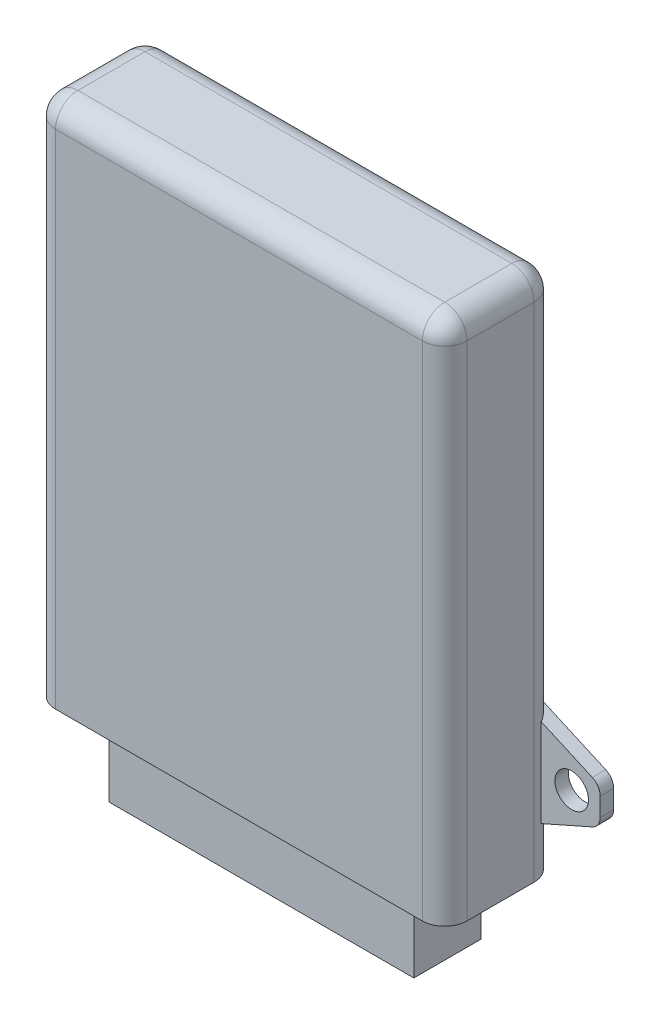
SolidWorks part; units mm, degrees
ref_plane "前视基准面" through (0, 0, 0) normal (0, 0, 1) x (1, 0, 0)
ref_plane "上视基准面" through (0, 0, 0) normal (0, 1, 0) x (1, 0, 0)
ref_plane "右视基准面" through (0, 0, 0) normal (1, 0, 0) x (0, 0, -1)
sketch "草图1" plane through (0, 0, 0) normal (0, 0, 1) x (1, 0, 0)
  line L1 (-37.9333, 65.9947) -> (44.0667, 65.9947)
  line L2 (-42.9333, 60.9947) -> (-42.9333, -51.3053)
  line L3 (-42.9333, -51.3053) -> (49.0667, -51.3053)
  line L4 (49.0667, 60.9947) -> (49.0667, -51.3053)
  arc A0 (49.0667, 60.9947) -> (44.0667, 65.9947) centre (44.0667, 60.9947) ccw
  arc A1 (-42.9333, 60.9947) -> (-37.9333, 65.9947) centre (-37.9333, 60.9947) cw
  point P6 (49.0667, 65.9947)
  point P9 (-42.9333, 65.9947)
  dimension "D3" = 5
  dimension "D1" = 92
  dimension "D2" = 117.3
extrude "凸台-拉伸1" add sketch "草图1" along normal blind 25 contours L2 L3 L4 A0 L1 A1
fillet "圆角2" radius 5 5 edges at (49.0667, 4.8447, 25) (47.6022, 64.5302, 25) (3.0667, 65.9947, 25) (-41.4689, 64.5302, 25) (-42.9333, 4.8447, 25)
fillet "圆角3" radius 5 5 edges at (49.0667, 4.8447, 0) (47.6022, 64.5302, 0) (3.0667, 65.9947, 0) (-41.4689, 64.5302, 0) (-42.9333, 4.8447, 0)
sketch "草图2" plane through (0, -51.3053, 0) normal (0, -1, 0) x (1, 0, 0)
  line L0 (3.0667, 25) -> (3.0667, 0) construction
  line L1 (-37.9333, 25) -> (44.0667, 25) construction
  line L2 (-37.9333, 0) -> (44.0667, 0) construction
  line L3 (-42.9333, 12.5) -> (49.0667, 12.5) construction
  line L4 (-42.9333, 20) -> (-42.9333, 5) construction
  line L5 (49.0667, 20) -> (49.0667, 5) construction
  line L6 (3.0667, 20) -> (3.0667, 5) construction
  line L7 (-31.0333, 20) -> (37.1667, 20)
  line L8 (-31.0333, 20) -> (-31.0333, 5)
  line L9 (-31.0333, 5) -> (37.1667, 5)
  line L10 (37.1667, 20) -> (37.1667, 5)
  line L11 (-31.0333, 12.5) -> (37.1667, 12.5) construction
  point P20 (3.0667, 12.5)
  point P21 (3.0667, 12.5)
  dimension "D1" = 68.2
  dimension "D2" = 15
extrude "凸台-拉伸2" add sketch "草图2" along normal blind 17
sketch "草图3" plane through (0, 0, 0) normal (0, 0, -1) x (-1, 0, 0)
  line L0 (-3.0667, -31.3053) -> (-43.846, -31.3053) construction
  line L1 (37.9333, -51.3053) -> (-44.0667, -51.3053) construction
  line L2 (-60.0654, -26.5211) -> (-43.846, -19.3053)
  line L3 (-3.0667, -51.3053) -> (-3.0667, -31.3053) construction
  line L4 (-43.846, -31.3053) -> (-43.846, -19.3053)
  line L5 (-43.846, -31.3053) -> (-43.846, -43.3053)
  line L6 (-49.0667, -51.3053) -> (-49.0667, 60.9947) construction
  line L7 (-61.846, -29.2621) -> (-61.846, -33.3629)
  line L8 (-60.0634, -36.1047) -> (-43.846, -43.3053)
  line L9 (-61.846, -31.3125) -> (-49.0667, -31.3125) construction
  circle A1 centre (-55.4563, -31.3125) radius 3.75
  arc A2 (-60.0634, -36.1047) -> (-61.846, -33.3629) centre (-58.846, -33.3629) cw
  arc A3 (-61.846, -29.2621) -> (-60.0654, -26.5211) centre (-58.846, -29.2621) cw
  point P12 (-61.846, -31.3125)
  point P19 (-61.846, -35.3133)
  point P22 (-61.846, -27.3133)
  dimension "D7" = 7.5
  dimension "D8" = 3
  dimension "D1" = 20
  dimension "D2" = 12
  dimension "D3" = 12
  dimension "D4" = 18
  dimension "D5" = 8
  dimension "D6" = 40.7793
extrude "凸台-拉伸3" add sketch "草图3" against normal blind 3
sketch "草图4" plane through (0, 0, 0) normal (0, 0, 1) x (1, 0, 0)
  line L0 (3.0667, -51.3053) -> (3.0667, 60.9947) construction
  line L1 (-31.0333, -51.3053) -> (37.1667, -51.3053) construction
  line L2 (-37.9333, 60.9947) -> (44.0667, 60.9947) construction
ref_plane "基准面1" through (3.0667, 0, 0) normal (1, 0, 0) x (0, 1, 0)
mirror "镜向1" about plane through (3.0667, 0, 0) normal (1, 0, 0) of "凸台-拉伸3"
